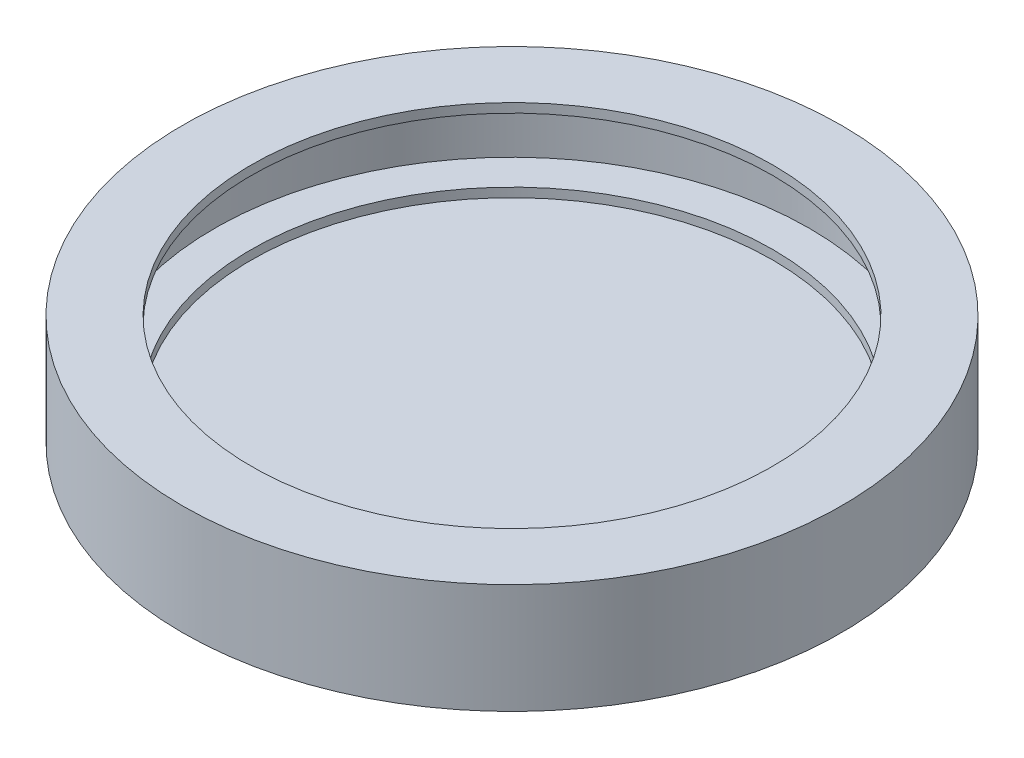
SolidWorks part; units mm, degrees
ref_plane "Front Plane" through (0, 0, 0) normal (0, 0, 1) x (1, 0, 0)
ref_plane "Top Plane" through (0, 0, 0) normal (0, 1, 0) x (1, 0, 0)
ref_plane "Right Plane" through (0, 0, 0) normal (1, 0, 0) x (0, 0, -1)
sketch "Sketch1" plane through (0, 0, 0) normal (1, 0, 0) x (0, 0, -1)
  line L0 (0, 0) -> (0, 46.1315) construction
  line L1 (0, 0) -> (0, 3)
  line L2 (0, 3) -> (-28.5, 3)
  line L3 (-28.5, 3) -> (-28.5, 4)
  line L4 (-28.5, 4) -> (-32.5, 4)
  line L5 (-32.5, 4) -> (-32.5, 11)
  line L6 (-32.5, 11) -> (-28.5, 11)
  line L7 (-28.5, 11) -> (-28.5, 12)
  line L8 (-28.5, 12) -> (-36, 12)
  line L9 (-36, 12) -> (-36, 0)
  line L10 (-36, 0) -> (0, 0)
  dimension "D1" = 7
  dimension "D2" = 4
  dimension "D3" = 4
  dimension "D4" = 1
  dimension "D5" = 32.5
  dimension "D6" = 36
  dimension "D7" = 3
  dimension "D8" = 12
revolve "Revolve1" add sketch "Sketch1" angle 360 about L0
